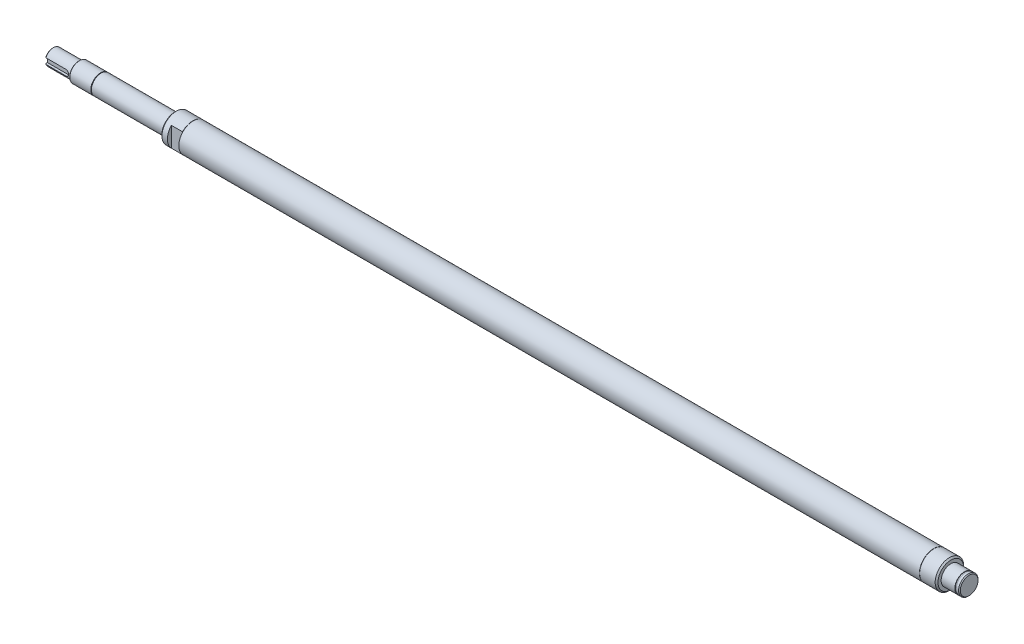
SolidWorks part; units mm, degrees
material "Plain Carbon Steel"
ref_plane "Front Plane" through (0, 0, 0) normal (0, 0, 1) x (1, 0, 0)
ref_plane "Top Plane" through (0, 0, 0) normal (0, 1, 0) x (1, 0, 0)
ref_plane "Right Plane" through (0, 0, 0) normal (1, 0, 0) x (0, 0, -1)
sketch "Sketch1" plane through (0, 0, 0) normal (0, 0, 1) x (1, 0, 0)
  line L0 (-6, 12.5) -> (-6, 0)
  line L1 (-6, 0) -> (689, 0)
  line L2 (689, 0) -> (689, 8.5)
  line L3 (689, 8.5) -> (686.15, 8.5)
  line L4 (686.15, 8.5) -> (686.15, 8.15)
  line L5 (686.15, 8.15) -> (685, 8.15)
  line L6 (685, 8.15) -> (685, 8.5)
  line L7 (685, 8.5) -> (673, 8.5)
  line L8 (673, 8.5) -> (673, 12.5)
  line L9 (673, 12.5) -> (658.2, 12.5)
  line L10 (658.2, 12.5) -> (658.2, 12.25)
  line L11 (658.2, 12.25) -> (658, 12.25)
  line L12 (658, 12.25) -> (658, 12.5)
  line L13 (658, 12.5) -> (10, 12.5)
  line L14 (10, 12.5) -> (10, 12.25)
  line L15 (10, 12.25) -> (9.8, 12.25)
  line L16 (9.8, 12.25) -> (9.8, 12.5)
  line L17 (9.8, 12.5) -> (-6, 12.5)
  line L18 (-6, 0) -> (689, 0) construction
  line L19 (560, 12.5) -> (560, 3.4335) construction
  dimension "D1" = 6
  dimension "D2" = 12.5
  dimension "D3" = 12.25
  dimension "D4" = 16
  dimension "D5" = 0.2
  dimension "D6" = 98
  dimension "D7" = 15
  dimension "D8" = 0.2
  dimension "D9" = 13.15
  dimension "D10" = 16
  dimension "D11" = 8.5
  dimension "D12" = 8.15
  dimension "D13" = 1.15
  dimension "D14" = 550
revolve "Revolve1" add sketch "Sketch1" angle 360 about L18
sketch "Sketch2" plane through (-6, 0, 0) normal (-1, 0, 0) x (0, 0, 1)
  circle A0 centre (0, 0) radius 8.5
  dimension "D1" = 17
extrude "Extrude1" add sketch "Sketch2" along normal blind 84
sketch "Sketch3" plane through (-90, 0, 0) normal (-1, 0, 0) x (0, 0, 1)
  circle A0 centre (0, 0) radius 7
  dimension "D1" = 14
extrude "Extrude2" add sketch "Sketch3" along normal blind 23
sketch "Sketch4" plane through (-113, 0, 0) normal (-1, 0, 0) x (0, 0, 1)
  line L0 (7.0711, 2.5) -> (4.5, 2.5)
  line L1 (4.5, 2.5) -> (4.5, -2.5)
  line L2 (4.5, -2.5) -> (7.0711, -2.5)
  arc A0 (7.0711, -2.5) -> (7.0711, 2.5) centre (0, 0) ccw
sketch "Sketch5" plane through (-6, 0, 0) normal (1, 0, 0) x (0, 0, -1)
  line L0 (9, 8.6747) -> (9, -8.6747)
  circle A1 centre (0, 0) radius 12.5 construction
  arc A2 (9, -8.6747) -> (9, 8.6747) centre (0, 0) ccw
  dimension "D1" = 9
extrude "Extrude4" cut sketch "Sketch5" along normal blind 10 from offset 6
ref_plane "Plane1" through (-10, 0, 0) normal (-1, 0, 0) x (0, -1, 0)
sketch "Sketch6" plane through (-6, 0, 0) normal (-1, 0, 0) x (0, -1, 0)
  line L0 (-8.6747, 9) -> (8.6747, 9)
  circle A1 centre (0, 0) radius 12.5 construction
  arc A2 (8.6747, 9) -> (-8.6747, 9) centre (0, 0) ccw
  dimension "D1" = 9
extrude "Extrude5" cut sketch "Sketch6" against normal blind 10 from offset 6 offset against normal yes
chamfer "Chamfer1" distance 0.6135 angle 45 1 edges at (-90, 0, 8.5)
chamfer "Chamfer2" distance 0.8333 angle 45 1 edges at (-113, 0, 7)
chamfer "Chamfer4" distance 0.75 angle 45 1 edges at (689, 0, -8.5)
chamfer "Chamfer5" distance 1.25 angle 45 1 edges at (673, 0, -12.5)
extrude "Extrude6" cut sketch "Sketch4" against normal blind 18.5
sketch "Sketch7" plane through (0, 0, 4.5) normal (0, 0, 1) x (1, 0, 0)
  line L0 (-94.5, 2.5) -> (-94.5, -2.5) construction
  circle A0 centre (-94.5, 0) radius 2.5
extrude "Extrude7" cut sketch "Sketch7" along normal blind 7.62
sketch "Sketch8" plane through (0, 0, 0) normal (0, 1, 0) x (1, 0, 0)
  line L0 (-6, 8.5) -> (-89.3865, 8.5) construction
  line L1 (-71, 8.5) -> (-70.5, 8.5)
  line L2 (-71, 8.5) -> (-71, 7.8)
  line L3 (-71, 7.8) -> (-70.5, 7.8)
  line L4 (-70.5, 8.5) -> (-70.5, 7.8)
  line L5 (-90, 7) -> (-90, -7) construction
  line L6 (0, 0) -> (-102.0056, 0) construction
  dimension "D1" = 0.5
  dimension "D2" = 0.7
  dimension "D3" = 19
revolve "Cut-Revolve1" cut sketch "Sketch8" angle 360 about L6
chamfer "Chamfer6" distance 1.25 angle 45 1 edges at (-6, 0, -12.5)
other "Freeze***"
